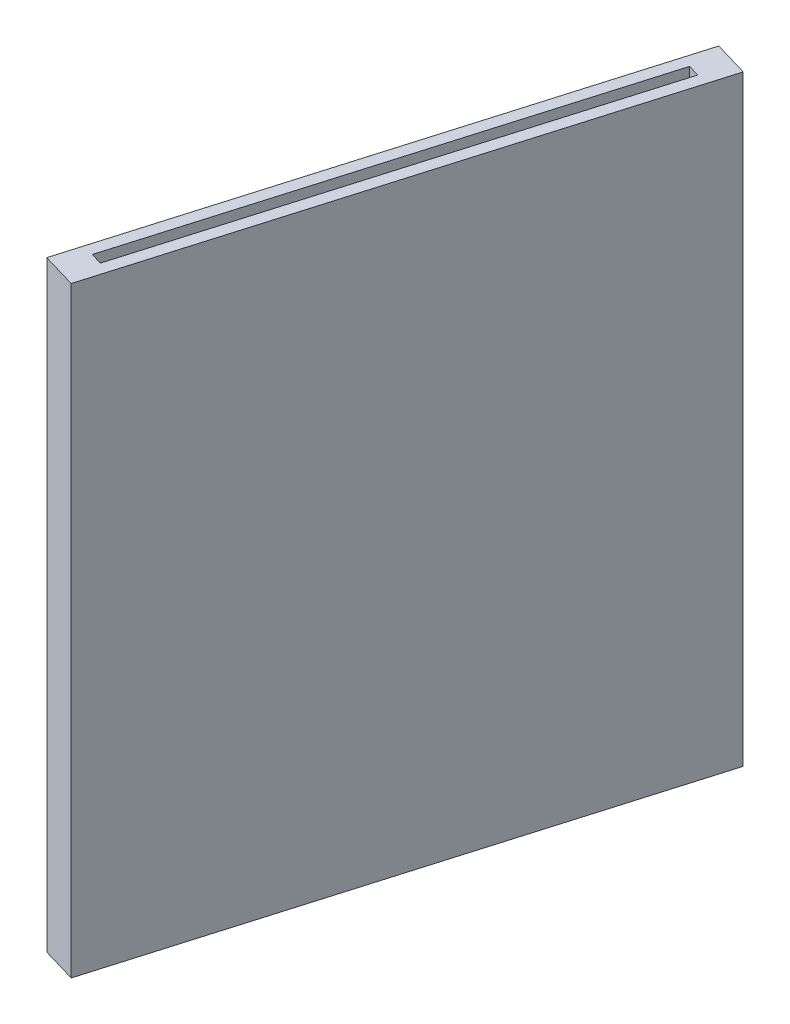
SolidWorks part; units mm, degrees
material "Glass"
ref_plane "Front Plane" through (0, 0, 0) normal (0, 0, 1) x (1, 0, 0)
ref_plane "Top Plane" through (0, 0, 0) normal (0, 1, 0) x (1, 0, 0)
ref_plane "Right Plane" through (0, 0, 0) normal (1, 0, 0) x (0, 0, -1)
sketch "Sketch5" plane through (0, 0, 0) normal (0, 1, 0) x (1, 0, 0)
  line L2 (-35.9068, -108.5804) -> (-28.5964, -110.7305)
  line L4 (-28.5964, -110.7305) -> (3.6552, -1.0751)
  line L6 (3.6552, -1.0751) -> (-3.6552, 1.0751)
  line L7 (-3.6552, 1.0751) -> (-35.9068, -108.5804)
  line L8 (-3.0102, -5.7336) -> (-0.5734, -6.4503)
  line L9 (-0.5734, -6.4503) -> (-29.2415, -103.9219)
  line L10 (-29.2415, -103.9219) -> (-31.6782, -103.2052)
  line L11 (-31.6782, -103.2052) -> (-3.0102, -5.7336)
  line L12 (-21.7591, 0) -> (21.7591, 0) construction
  point P2 (0, 0)
  point P3 (0, 0)
  dimension "D1" = 7.62
  dimension "D2" = 6.35
  dimension "D3" = 101.6
  dimension "D4" = 6.35
  dimension "D5" = 2.54
  dimension "D6" = 2.54
  dimension "D7" = 16.39
extrude "Boss-Extrude1" add sketch "Sketch5" against normal blind 127
